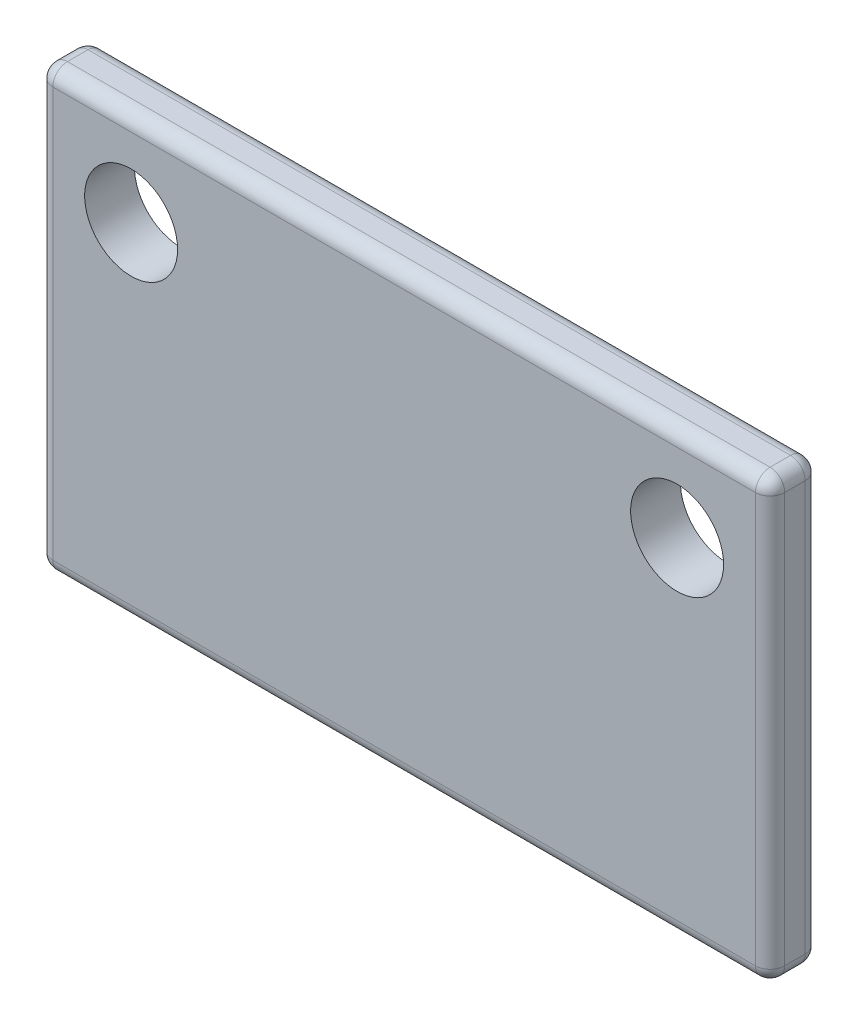
SolidWorks part; units mm, degrees
ref_plane "Plano frontal" through (0, 0, 0) normal (0, 0, 1) x (1, 0, 0)
ref_plane "Plano superior" through (0, 0, 0) normal (0, 1, 0) x (1, 0, 0)
ref_plane "Plano direito" through (0, 0, 0) normal (1, 0, 0) x (0, 0, -1)
sketch "Esboço1" plane through (0, 0, 0) normal (0, 0, 1) x (1, 0, 0)
  line L1 (12.5, -7.5) -> (-12.5, -7.5)
  line L2 (12.5, -7.5) -> (12.5, 7.5)
  line L3 (12.5, 7.5) -> (-12.5, 7.5)
  line L4 (-12.5, -7.5) -> (-12.5, 7.5)
  line L5 (12.5, -7.5) -> (-12.5, 7.5) construction
  line L6 (12.5, 7.5) -> (-12.5, -7.5) construction
  point P0 (0, 0)
  dimension "D1" = 25
  dimension "D2" = 15
extrude "Ressalto-extrusão1" add sketch "Esboço1" along normal blind 1.7
sketch "Esboço2" plane through (0, 0, 1.7) normal (0, 0, 1) x (1, 0, 0)
  line L1 (-12.5, 7.5) -> (-9.325, 7.5) construction
  line L2 (-12.5, 7.5) -> (-12.5, 4.325) construction
  line L3 (-12.5, 4.325) -> (-9.325, 4.325) construction
  line L4 (-12.5, 7.5) -> (-12.5, -7.5)
  line L5 (-12.5, -7.5) -> (12.5, -7.5)
  line L6 (12.5, -7.5) -> (12.5, 7.5)
  line L7 (12.5, 7.5) -> (-12.5, 7.5)
  line L8 (-12.5, 7.5) -> (-12.5, -7.5) construction
  line L9 (-12.5, -7.5) -> (12.5, -7.5)
  line L10 (12.5, -7.5) -> (12.5, 7.5) construction
  line L11 (12.5, 7.5) -> (-12.5, 7.5) construction
  line L12 (-9.325, 7.5) -> (-9.325, 4.325) construction
  line L13 (12.5, 7.5) -> (9.325, 7.5) construction
  line L14 (12.5, 7.5) -> (12.5, 4.325) construction
  line L15 (12.5, 4.325) -> (9.325, 4.325) construction
  line L16 (9.325, 7.5) -> (9.325, 4.325) construction
  circle A0 centre (-9.325, 4.325) radius 1.5875
  circle A1 centre (9.325, 4.325) radius 1.5875
  dimension "D3" = 3.175
  dimension "D2" = 3.175
  dimension "D1" = 0
extrude "Corte-extrusão1" cut sketch "Esboço2" against normal through all contours A0 | A1
fillet "Filete2" radius 0.5 12 edges at (0, -7.5, 0) (12.5, 0, 0) (-12.5, 0, 1.7) (0, -7.5, 1.7) (12.5, 0, 1.7) (0, 7.5, 1.7) (12.5, 7.5, 0.85) (12.5, -7.5, 0.85) (-12.5, -7.5, 0.85) (-12.5, 7.5, 0.85) (-12.5, 0, 0) (0, 7.5, 0)
